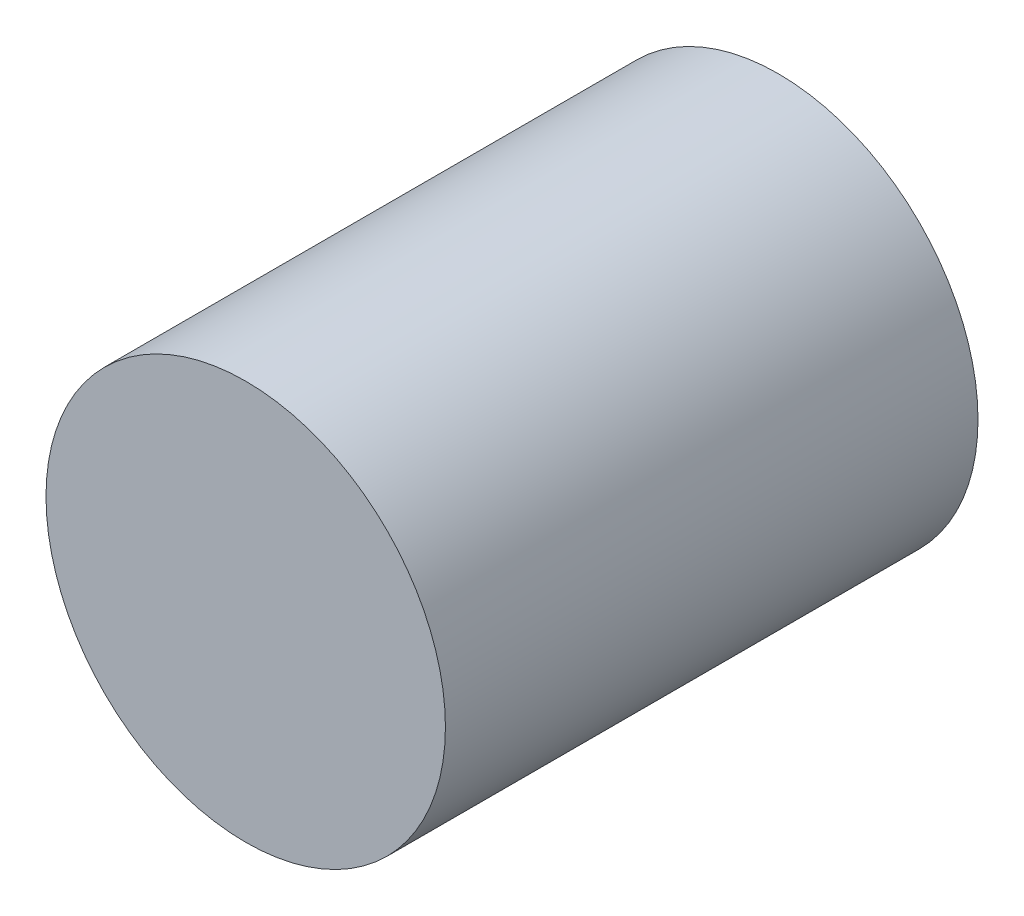
SolidWorks part; units mm, degrees
ref_plane "Front Plane" through (0, 0, 0) normal (0, 0, 1) x (1, 0, 0)
ref_plane "Top Plane" through (0, 0, 0) normal (0, 1, 0) x (1, 0, 0)
ref_plane "Right Plane" through (0, 0, 0) normal (1, 0, 0) x (0, 0, -1)
sketch "Sketch1" plane through (0, 0, 0) normal (0, 0, 1) x (1, 0, 0)
  circle A0 centre (0, 0) radius 19.05
extrude "Boss-Extrude1" add sketch "Sketch1" along normal blind 50.8
